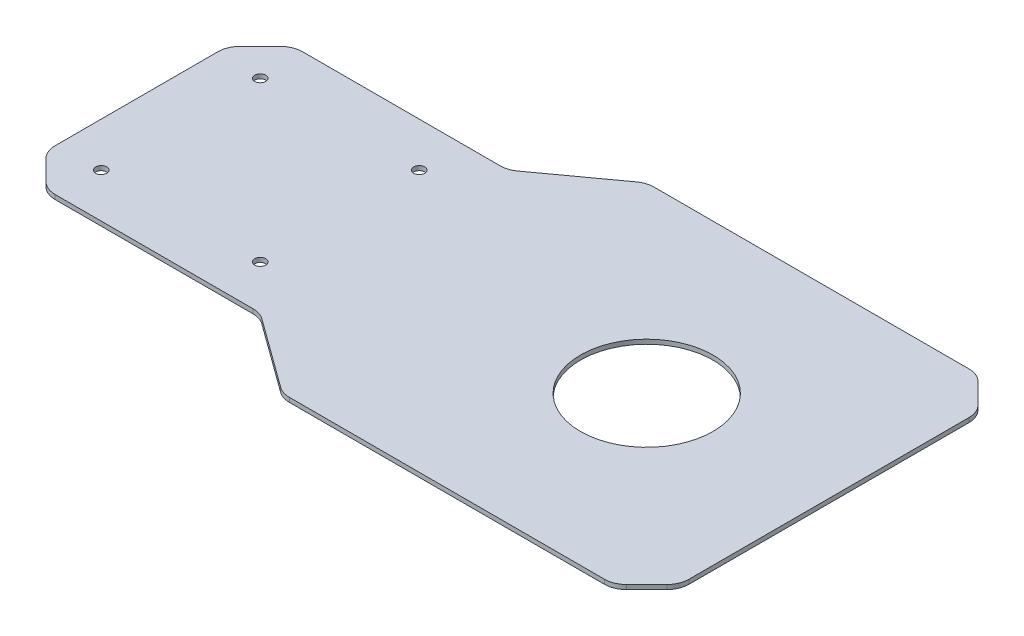
SolidWorks part; units mm, degrees
material "1060 Alloy"
ref_plane "Front Plane" through (0, 0, 0) normal (0, 0, 1) x (1, 0, 0)
ref_plane "Top Plane" through (0, 0, 0) normal (0, 1, 0) x (1, 0, 0)
ref_plane "Right Plane" through (0, 0, 0) normal (1, 0, 0) x (0, 0, -1)
sketch "Sketch2" plane through (0, 0, 0) normal (0, 1, 0) x (1, 0, 0)
  line L0 (56, 56) -> (92.5, 82.5)
  line L1 (-56, 56) -> (56, 56)
  line L2 (-56, 56) -> (-56, -56)
  line L3 (-56, -56) -> (56, -56)
  line L4 (56, 56) -> (56, -56) construction
  line L5 (-56, 56) -> (56, -56) construction
  line L6 (-56, -56) -> (56, 56) construction
  line L7 (92.5, 82.5) -> (257.5, 82.5)
  line L8 (92.5, 82.5) -> (92.5, -82.5) construction
  line L9 (92.5, -82.5) -> (257.5, -82.5)
  line L10 (257.5, 82.5) -> (257.5, -82.5)
  line L11 (92.5, 82.5) -> (257.5, -82.5) construction
  line L12 (92.5, -82.5) -> (257.5, 82.5) construction
  line L13 (56, -56) -> (92.5, -82.5)
  point P0 (0, 0)
  point P1 (175, 0)
  point P3 (175, 0)
  point P5 (0, 0)
  dimension "D1" = 175
  dimension "D2" = 112
  dimension "D3" = 165
extrude "Boss-Extrude1" add sketch "Sketch2" along normal blind 2
chamfer "Chamfer1" distance 15 angle 45 4 edges at (-56, 1, -56) (-56, 1, 56) (257.5, 1, -82.5) (257.5, 1, 82.5)
fillet "Fillet1" radius 10 12 edges at (56, 1, 56) (56, 1, -56) (92.5, 1, -82.5) (92.5, 1, 82.5) (-56, 1, 41) (-41, 1, 56) (-56, 1, -41) (-41, 1, -56) (242.5, 1, -82.5) (257.5, 1, -67.5) (257.5, 1, 67.5) (242.5, 1, 82.5)
sketch "Sketch3" plane through (0, 2, 0) normal (0, 1, 0) x (1, 0, 0)
  circle A0 centre (36, 36) radius 2.5
  circle A1 centre (-36, 36) radius 2.5
  circle A2 centre (-36, -36) radius 2.5
  circle A3 centre (36, -36) radius 2.5
  circle A4 centre (175, 0) radius 30
  point P3 (0, 0)
  dimension "D1" = 5
  dimension "D8" = 60
  dimension "D2" = 36
  dimension "D3" = 36
  dimension "D6" = 72
  dimension "D7" = 72
  dimension "D9" = 175
  dimension "D4" = 2
  dimension "D5" = 2
extrude "Cut-Extrude1" cut sketch "Sketch3" against normal through all
equation "\"Drive Pulley Diameter\"= 50mm"
equation "\"Transfer Pulley Diameter\"= 100mm"
equation "\"Belt Distance\"= 175mm"
equation "\"Extra Spacing\"= 15mm"
equation "\"Drive Pulley Radius\"= \"Drive Pulley Diameter\" / 2"
equation "\"Transfer Pulley Radius\"= \"Transfer Pulley Diameter\" / 2"
equation "\"Base Thickness\"= 5mm"
equation "\"Stepper Mount Width\"= 97mm"
equation "\"D2@Sketch2\"=\"Stepper Mount Width\"+\"Extra Spacing\""
equation "\"Elevator Diameter\"= 150mm"
equation "\"D3@Sketch2\"=\"Elevator Diameter\"+\"Extra Spacing\""
equation "\"Motor Mount Screw Diameter\"= 5mm"
equation "\"D1@Sketch3\"=\"Motor Mount Screw Diameter\""
equation "\"Motor Mount Screw X-Dist\"= 72 / 2mm"
equation "\"Motor Mount Screw Y-Dist\"= 72 / 2mm"
equation "\"D2@Sketch3\"=\"Motor Mount Screw Y-Dist\""
equation "\"D6@Sketch3\"=\"Motor Mount Screw X-Dist\"*2"
equation "\"D7@Sketch3\"=\"Motor Mount Screw Y-Dist\"*2"
equation "\"Bearing Diameter\"= 60mm"
equation "\"D9@Sketch3\"=\"Belt Distance\""
equation "\"D8@Sketch3\"=\"Bearing Diameter\""
